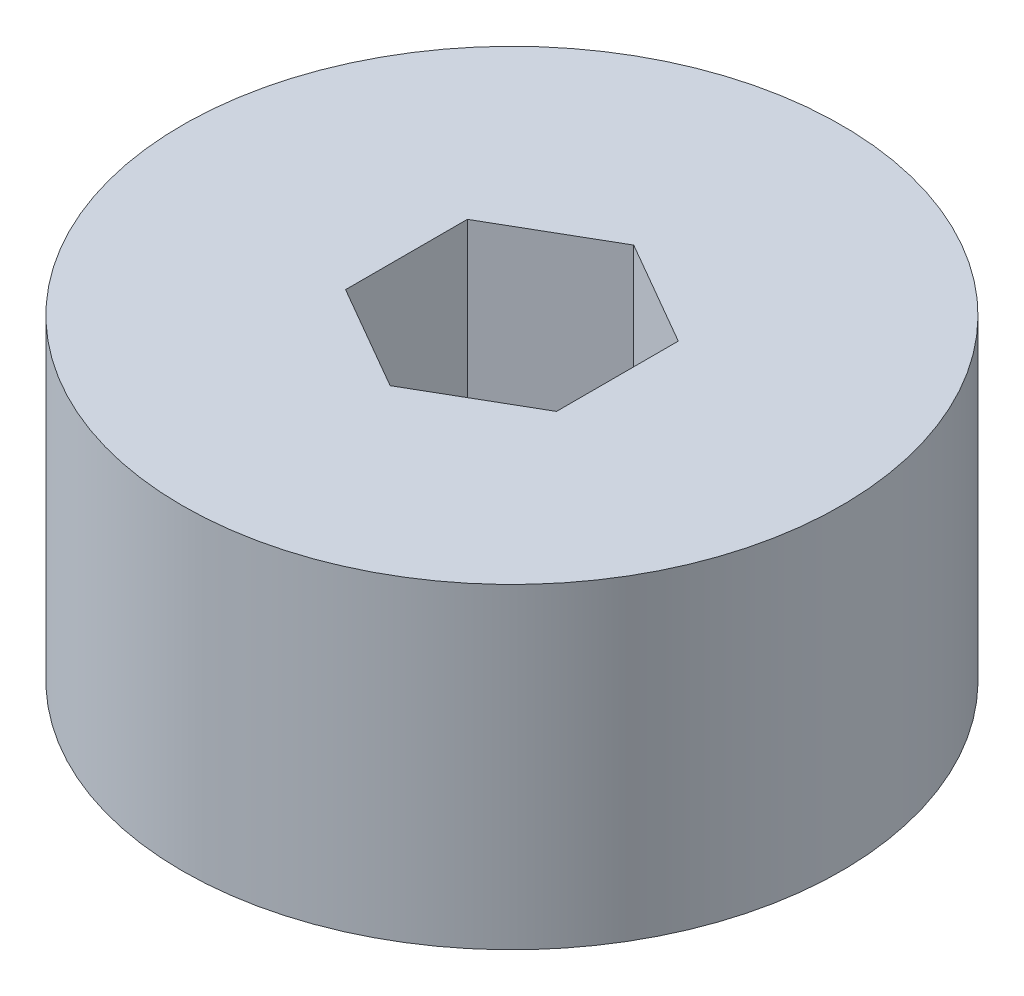
SolidWorks part; units mm, degrees
ref_plane "Front Plane" through (0, 0, 0) normal (0, 0, 1) x (1, 0, 0)
ref_plane "Top Plane" through (0, 0, 0) normal (0, 1, 0) x (1, 0, 0)
ref_plane "Right Plane" through (0, 0, 0) normal (1, 0, 0) x (0, 0, -1)
sketch "Sketch1" plane through (0, 0, 0) normal (0, 1, 0) x (1, 0, 0)
  circle A0 centre (0, 0) radius 12.5
  dimension "D1" = 25
extrude "Boss-Extrude1" add sketch "Sketch1" along normal blind 12
sketch "Sketch2" plane through (0, 12, 0) normal (0, 1, 0) x (1, 0, 0)
  line L1 (0, -4.6188) -> (4, -2.3094)
  line L2 (4, -2.3094) -> (4, 2.3094)
  line L3 (4, 2.3094) -> (0, 4.6188)
  line L4 (0, 4.6188) -> (-4, 2.3094)
  line L5 (-4, 2.3094) -> (-4, -2.3094)
  line L6 (-4, -2.3094) -> (0, -4.6188)
  circle A0 centre (0, 0) radius 4 construction
  dimension "D1" = 8
extrude "Cut-Extrude1" cut sketch "Sketch2" against normal blind 8.2
